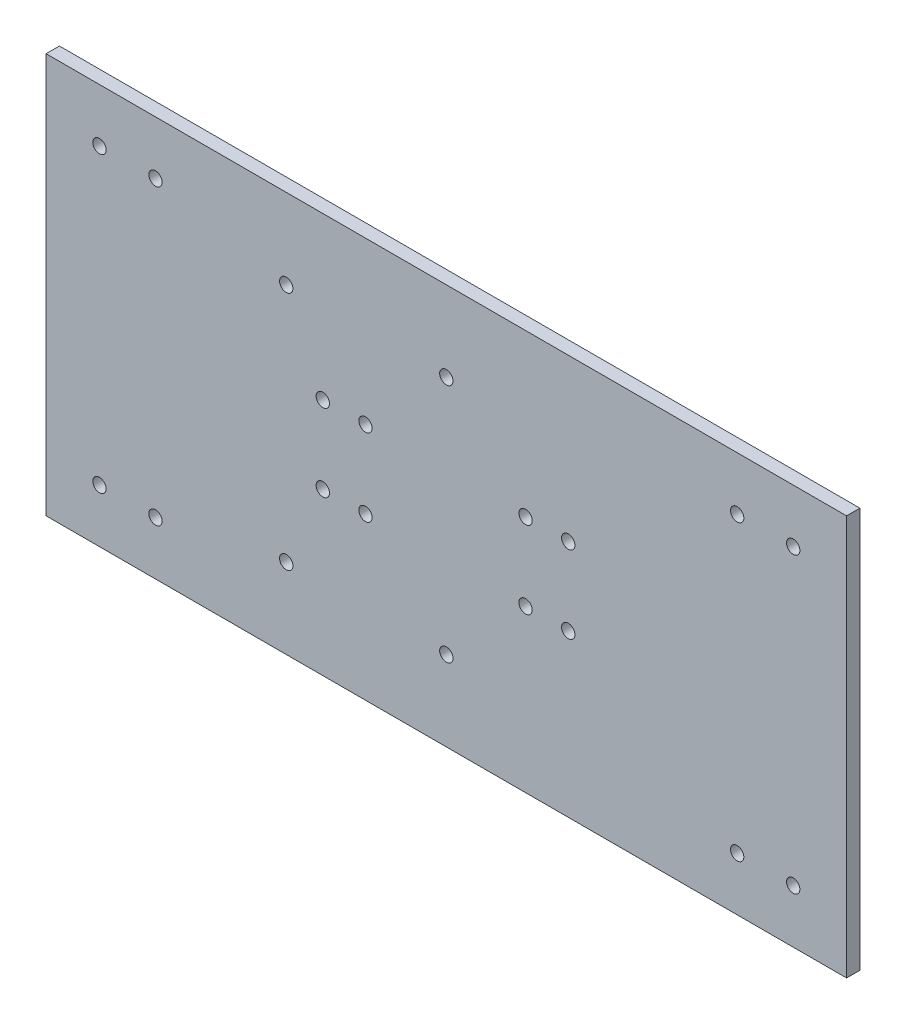
SolidWorks part; units mm, degrees
ref_plane "Plan de face" through (0, 0, 0) normal (0, 0, 1) x (1, 0, 0)
ref_plane "Plan de dessus" through (0, 0, 0) normal (0, 1, 0) x (1, 0, 0)
ref_plane "Plan de droite" through (0, 0, 0) normal (1, 0, 0) x (0, 0, -1)
sketch "Esquisse1" plane through (0, 0, 0) normal (0, 0, 1) x (1, 0, 0)
  line L1 (0, 0) -> (300, 0)
  line L2 (0, 0) -> (0, 150)
  line L3 (0, 150) -> (300, 150)
  line L4 (300, 0) -> (300, 150)
  circle A0 centre (150, 30) radius 2.5
  circle A1 centre (150, 120) radius 2.5
  circle A2 centre (103.7, 89.5) radius 2.5
  circle A3 centre (103.7, 60.5) radius 2.5
  circle A4 centre (119.7, 89.5) radius 2.5
  circle A5 centre (119.7, 60.5) radius 2.5
  circle A6 centre (90, 120) radius 2.5
  circle A7 centre (90, 30) radius 2.5
  circle A8 centre (179.7, 89.5) radius 2.5
  circle A11 centre (179.7, 60.5) radius 2.5
  circle A12 centre (195.7, 89.5) radius 2.5
  circle A13 centre (195.7, 60.5) radius 2.5
  circle A14 centre (20, 130) radius 2.5
  circle A15 centre (41, 130) radius 2.5
  circle A16 centre (259, 130) radius 2.5
  circle A17 centre (280, 130) radius 2.5
  circle A18 centre (259, 20) radius 2.5
  circle A19 centre (280, 20) radius 2.5
  circle A20 centre (20, 20) radius 2.5
  circle A21 centre (41, 20) radius 2.5
  dimension "D3" = 150
  dimension "D5" = 5
  dimension "D6" = 5
  dimension "D9" = 5
  dimension "D10" = 5
  dimension "D15" = 5
  dimension "D16" = 5
  dimension "D21" = 5
  dimension "D24" = 5
  dimension "D35" = 5
  dimension "D36" = 5
  dimension "D37" = 5
  dimension "D38" = 5
  dimension "D39" = 20
  dimension "D41" = 21
  dimension "D42" = 5
  dimension "D43" = 5
  dimension "D1" = 300
  dimension "D2" = 150
  dimension "D4" = 150
  dimension "D7" = 90
  dimension "D8" = 30
  dimension "D11" = 30.5
  dimension "D12" = 30.5
  dimension "D13" = 46.3
  dimension "D14" = 46.3
  dimension "D17" = 16
  dimension "D18" = 16
  dimension "D19" = 30.5
  dimension "D20" = 30.5
  dimension "D22" = 60
  dimension "D23" = 30
  dimension "D25" = 60
  dimension "D26" = 30
  dimension "D27" = 60
  dimension "D28" = 60
  dimension "D29" = 16
  dimension "D30" = 16
  dimension "D31" = 0
  dimension "D32" = 0
  dimension "D33" = 0
  dimension "D34" = 0
  dimension "D40" = 20
  dimension "D44" = 2
  dimension "D45" = 2
extrude "Boss.-Extru.1" add sketch "Esquisse1" along normal blind 5
